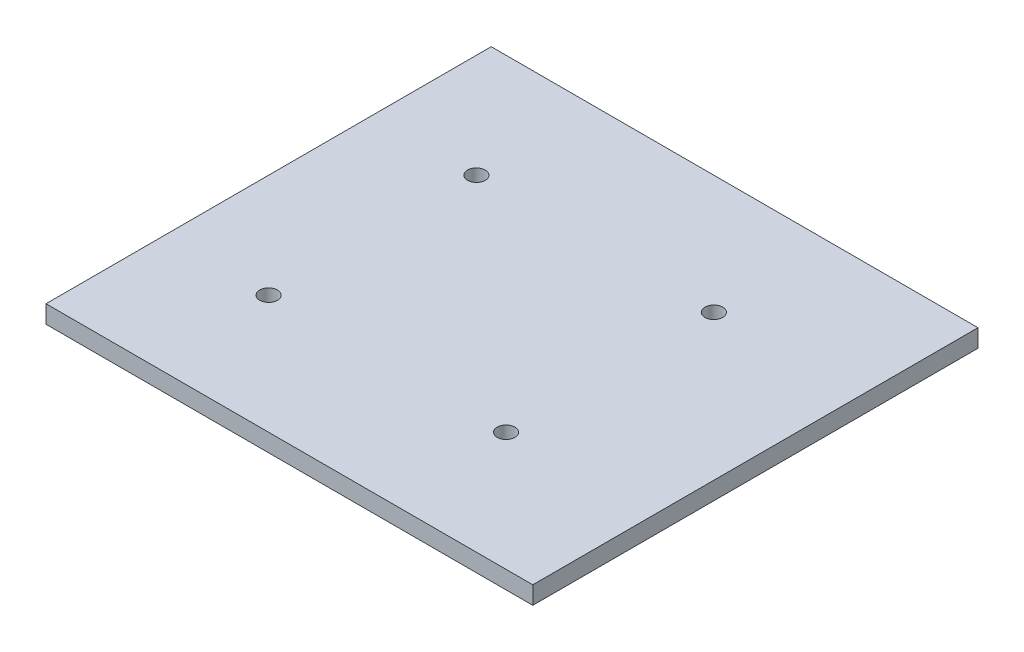
SolidWorks part; units mm, degrees
material "Glass"
ref_plane "Front Plane" through (0, 0, 0) normal (0, 0, 1) x (1, 0, 0)
ref_plane "Top Plane" through (0, 0, 0) normal (0, 1, 0) x (1, 0, 0)
ref_plane "Right Plane" through (0, 0, 0) normal (1, 0, 0) x (0, 0, -1)
sketch "Sketch1" plane through (0, 0, 0) normal (0, 1, 0) x (1, 0, 0)
  line L1 (0, 0) -> (82, 0)
  line L2 (0, 0) -> (0, 75)
  line L3 (0, 75) -> (82, 75)
  line L4 (82, 0) -> (82, 75)
  dimension "D1" = 75
  dimension "D2" = 82
extrude "Boss-Extrude1" add sketch "Sketch1" along normal blind 3
sketch "Sketch5" plane through (0, 3, 0) normal (0, 1, 0) x (1, 0, 0)
  circle A0 centre (17.5, 55) radius 1.5
  circle A1 centre (57.5, 55) radius 1.5
  circle A2 centre (17.5, 20) radius 1.5
  circle A3 centre (57.5, 20) radius 1.5
  dimension "D5" = 3
  dimension "D1" = 40
  dimension "D2" = 35
extrude "Cut-Extrude2" cut sketch "Sketch5" against normal blind 3
